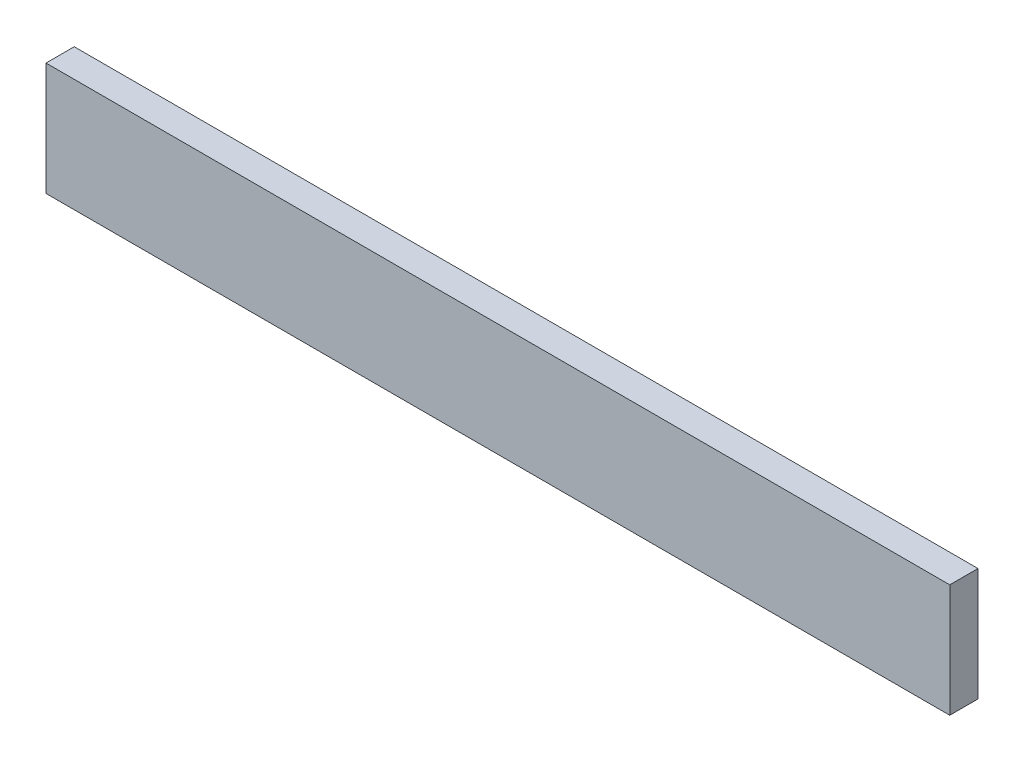
SolidWorks part; units mm, degrees
ref_plane "Alzado" through (0, 0, 0) normal (0, 0, 1) x (1, 0, 0)
ref_plane "Planta" through (0, 0, 0) normal (0, 1, 0) x (1, 0, 0)
ref_plane "Vista lateral" through (0, 0, 0) normal (1, 0, 0) x (0, 0, -1)
sketch "Croquis1" plane through (0, 0, 0) normal (0, 0, 1) x (1, 0, 0)
  line L1 (-160, -20) -> (160, -20)
  line L2 (-160, -20) -> (-160, 20)
  line L3 (-160, 20) -> (160, 20)
  line L4 (160, -20) -> (160, 20)
  line L5 (-160, -20) -> (160, 20) construction
  line L6 (-160, 20) -> (160, -20) construction
  point P0 (0, 0)
  dimension "D1" = 40
  dimension "D2" = 320
extrude "Saliente-Extruir1" add sketch "Croquis1" along normal mid plane 10
sketch "Croquis2" plane through (0, 0, 0) normal (0, 0, 1) x (1, 0, 0)
  line L0 (0, 20) -> (0, -20) construction
  line L1 (160, 20) -> (-160, 20) construction
  line L2 (-160, -20) -> (160, -20) construction
  line L3 (-160, 15) -> (160, 15) construction
  line L4 (-160, 20) -> (-160, -20) construction
  line L5 (160, -20) -> (160, 20) construction
  line L6 (155, 20) -> (155, -20) construction
  line L7 (-155, 20) -> (-155, -20) construction
  line L8 (-160, 0) -> (160, 0) construction
  line L9 (-160, -15) -> (160, -15) construction
  circle A0 centre (155, 15) radius 2.5
  circle A1 centre (77.5, 15) radius 2.5
  circle A2 centre (0, 15) radius 2.5
  circle A3 centre (-77.5, 15) radius 2.5
  circle A4 centre (-155, 15) radius 2.5
  circle A5 centre (155, -15) radius 2.5
  circle A6 centre (77.5, -15) radius 2.5
  circle A7 centre (0, -15) radius 2.5
  circle A8 centre (-77.5, -15) radius 2.5
  circle A9 centre (-155, -15) radius 2.5
  circle A10 centre (-155, 0) radius 2.5
  circle A11 centre (155, 0) radius 2.5
  dimension "D3" = 5
  dimension "D1" = 5
  dimension "D2" = 5
  dimension "D4" = 5
  dimension "D5" = 2
extrude "Cortar-Extruir1" cut sketch "Croquis2" against normal blind 5
